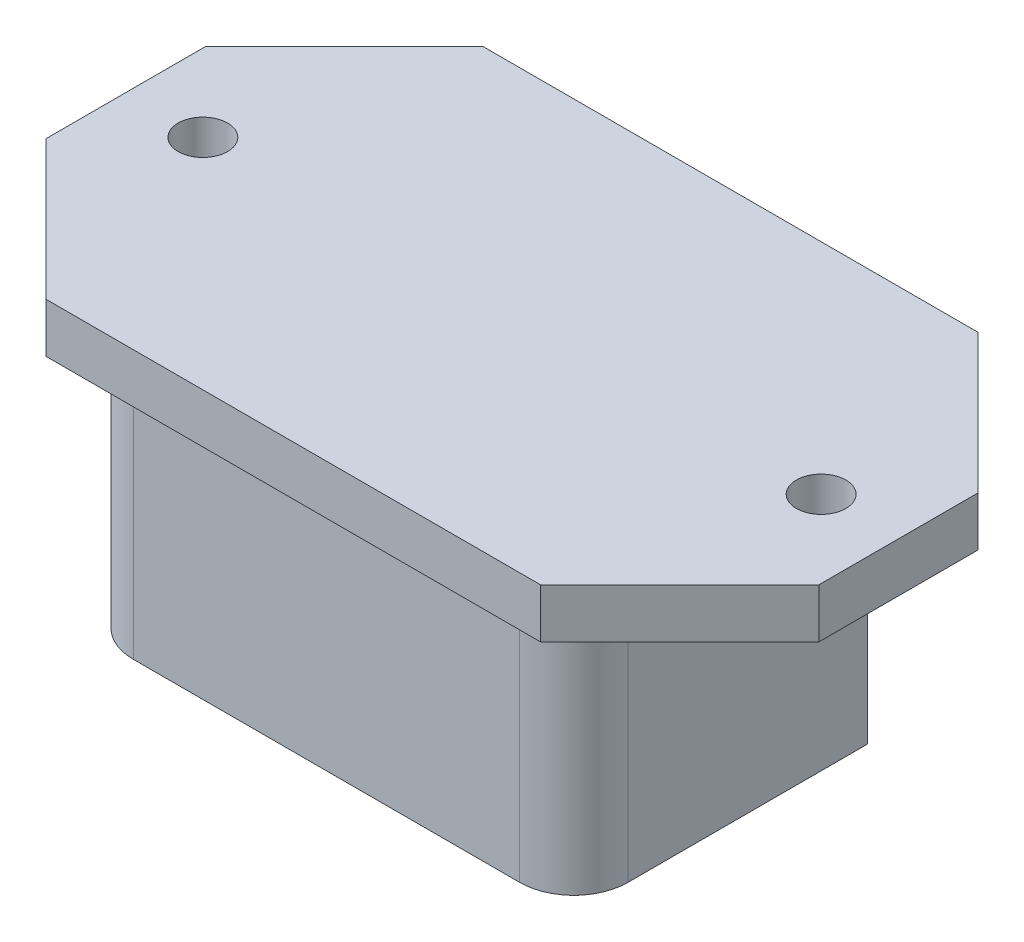
SolidWorks part; units mm, degrees
ref_plane "Front Plane" through (0, 0, 0) normal (0, 0, 1) x (1, 0, 0)
ref_plane "Top Plane" through (0, 0, 0) normal (0, 1, 0) x (1, 0, 0)
ref_plane "Right Plane" through (0, 0, 0) normal (1, 0, 0) x (0, 0, -1)
sketch "Sketch1" plane through (0, 0, 0) normal (0, 1, 0) x (1, 0, 0)
  line L1 (-16, -12) -> (16, -12)
  line L2 (-16, -12) -> (-16, 12)
  line L3 (-16, 12) -> (16, 12)
  line L4 (16, -12) -> (16, 12)
  line L5 (-16, -12) -> (16, 12) construction
  line L6 (-16, 12) -> (16, -12) construction
  point P0 (0, 0)
  dimension "D1" = 32
  dimension "D2" = 24
extrude "Boss-Extrude1" add sketch "Sketch1" along normal blind 16.3
sketch "Sketch2" plane through (0, 16.3, 0) normal (0, 1, 0) x (1, 0, 0)
  line L1 (-25, 14.15) -> (25, 14.15)
  line L2 (-25, 14.15) -> (-25, -14.15)
  line L3 (-25, -14.15) -> (25, -14.15)
  line L4 (25, 14.15) -> (25, -14.15)
  line L5 (-25, 14.15) -> (25, -14.15) construction
  line L6 (-25, -14.15) -> (25, 14.15) construction
  point P0 (0, 0)
  dimension "D1" = 50
  dimension "D2" = 28.3
extrude "Boss-Extrude2" add sketch "Sketch2" along normal blind 3.2
fillet "Fillet1" radius 3.5 2 edges at (-16, 8.15, 12) (16, 8.15, 12)
chamfer "Chamfer1" distance 5 angle 45 2 edges at (-16, 8.15, -12) (16, 8.15, -12)
chamfer "Chamfer2" distance 9 angle 45 4 edges at (25, 17.9, 14.15) (25, 17.9, -14.15) (-25, 17.9, 14.15) (-25, 17.9, -14.15)
sketch "Sketch3" plane through (0, 19.5, 0) normal (0, 1, 0) x (1, 0, 0)
  line L0 (0, 0) -> (50000, 0) construction
  line L1 (0, 0) -> (0, -50000) construction
  circle A0 centre (-20, 0) radius 1.6
  circle A1 centre (20, 0) radius 1.6
  dimension "D1" = 3.2
  dimension "D2" = 40
extrude "Cut-Extrude1" cut sketch "Sketch3" against normal blind 3.2
